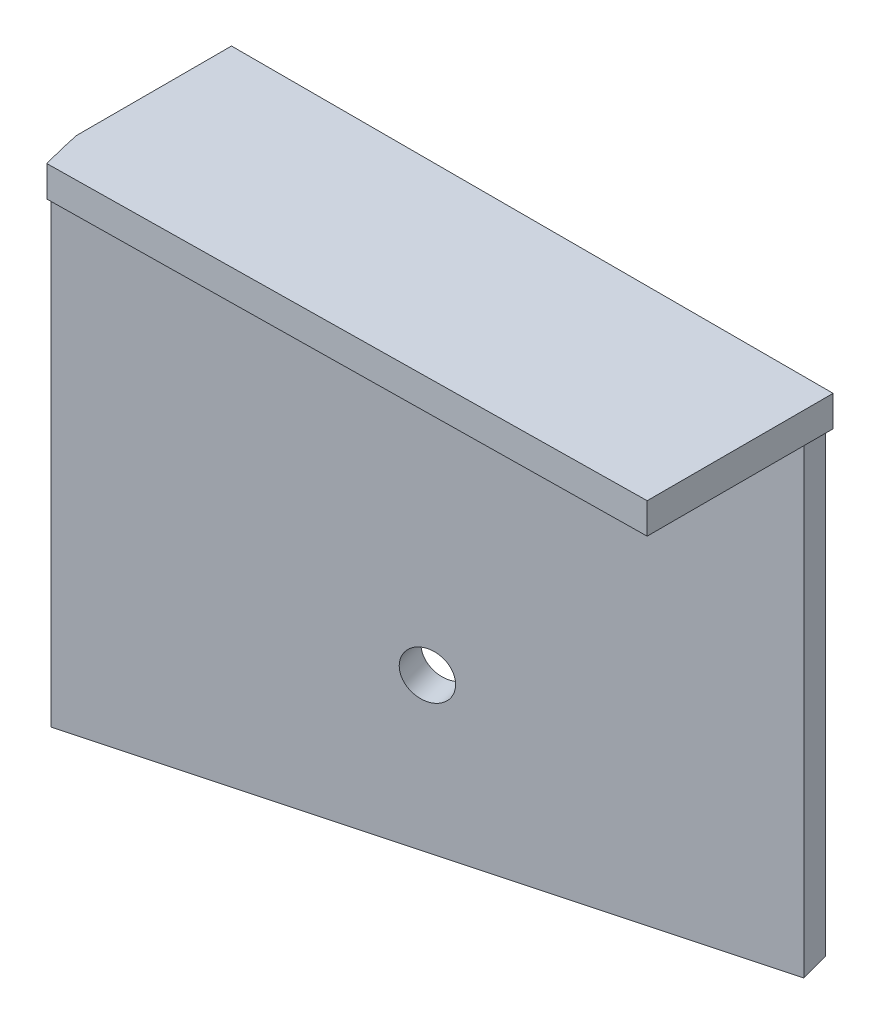
SolidWorks part; units mm, degrees
ref_plane "Front Plane" through (0, 0, 0) normal (0, 0, 1) x (1, 0, 0)
ref_plane "Top Plane" through (0, 0, 0) normal (0, 1, 0) x (1, 0, 0)
ref_plane "Right Plane" through (0, 0, 0) normal (1, 0, 0) x (0, 0, -1)
sketch "Sketch1" plane through (0, 0, 0) normal (0, 1, 0) x (1, 0, 0)
  line L0 (0, 0) -> (-80, 0)
  line L1 (-77.2741, -20.7055) -> (0, 0)
  arc A0 (-80, 0) -> (-77.2741, -20.7055) centre (0, 0) ccw
  dimension "D1" = 80
extrude "Boss-Extrude1" add sketch "Sketch1" along normal blind 4
sketch "Sketch7" plane through (0, 0, 0) normal (0, -1, 0) x (1, 0, 0)
  line L0 (0, 0) -> (-77.2741, 20.7055)
  line L1 (0, 0) -> (-1.0353, -3.8637)
  line L2 (-77.2741, 20.7055) -> (-78.3093, 16.8418)
  line L3 (-1.0353, -3.8637) -> (-78.3093, 16.8418)
  dimension "D1" = 4
extrude "Boss-Extrude3" add sketch "Sketch7" along normal blind 60
sketch "Sketch8" plane through (-1.0353, 0, -3.8637) normal (-0.2588, 0, -0.9659) x (-0.9659, 0, 0.2588)
  line L0 (0, -60) -> (80, -60) construction
  line L1 (80, -60) -> (80, 0) construction
  circle A0 centre (40, -40) radius 3
  dimension "D1" = 6
  dimension "D2" = 20
  dimension "D3" = 40
extrude "Cut-Extrude2" cut sketch "Sketch8" against normal blind 79
sketch "Sketch11" plane through (0, 4, 0) normal (0, 1, 0) x (1, 0, 0)
  line L0 (0, 0) -> (-77.2741, -20.7055)
  line L2 (0, 0) -> (0, -80)
  arc A0 (-77.2741, -20.7055) -> (0, -80) centre (0, 0) ccw
extrude "Boss-Extrude5" add sketch "Sketch11" against normal blind 4
sketch "Sketch12" plane through (0, 0, 0) normal (0, -1, 0) x (1, 0, 0)
  line L0 (-68.8303, 40.7724) -> (32.5658, 40.7724)
  line L1 (32.5658, 40.7724) -> (32.5658, 109.0472)
  line L2 (32.5658, 109.0472) -> (-78.5437, 109.0472)
  line L3 (-78.5437, 109.0472) -> (-68.8303, 40.7724)
  arc A0 (0, 80) -> (-77.2741, 20.7055) centre (0, 0) ccw construction
extrude "Cut-Extrude3" cut sketch "Sketch12" against normal blind 4
sketch "Sketch14" plane through (0, 0, 0) normal (0, -1, 0) x (1, 0, 0)
  line L0 (-78.3093, 16.8418) -> (-78.3093, -83.1582)
  line L1 (-78.3093, -83.1582) -> (-116.3713, -83.1582)
  line L2 (-116.3713, -83.1582) -> (-116.3713, 16.8418)
  line L3 (-116.3713, 16.8418) -> (-78.3093, 16.8418)
  dimension "D1" = 100
extrude "Cut-Extrude4" cut sketch "Sketch14" against normal blind 4
sketch "Sketch15" plane through (0, 0, 0) normal (0, -1, 0) x (-1, 0, 0)
  line L0 (81.8992, -21.5196) -> (0, -20.3862)
  line L1 (0, -40.7724) -> (0, 0) construction
  line L2 (0, -20.3862) -> (0, -64.2519)
  line L3 (0, -64.2519) -> (85.6847, -64.2519)
  line L4 (85.6847, -64.2519) -> (81.8992, -21.5196)
extrude "Cut-Extrude5" cut sketch "Sketch15" against normal blind 10
sketch "Sketch16" plane through (0, 0, 0) normal (0, 0, -1) x (-1, 0, 0)
  line L1 (0, 0) -> (78.3093, 0)
  line L2 (0, 0) -> (0, 4)
  line L3 (0, 4) -> (78.3093, 4)
  line L4 (78.3093, 0) -> (78.3093, 4)
extrude "Boss-Extrude6" add sketch "Sketch16" along normal blind 10
sketch "Sketch17" plane through (0, 0, 0) normal (0, -1, 0) x (-1, 0, 0)
  line L0 (1.2035, 3.8186) -> (78.3093, 3.8186)
  line L1 (78.2127, -16.8159) -> (1.0353, 3.8637) construction
  line L2 (78.3093, 10) -> (78.3093, -16.3599) construction
  line L3 (78.3093, 3.8186) -> (78.3093, 14.9544)
  line L4 (78.3093, 14.9544) -> (-14.1909, 13.3732)
  line L5 (-14.1909, 13.3732) -> (-14.1909, 3.8186)
  line L6 (-14.1909, 3.8186) -> (1.2035, 3.8186)
extrude "Cut-Extrude6" cut sketch "Sketch17" against normal blind 10
